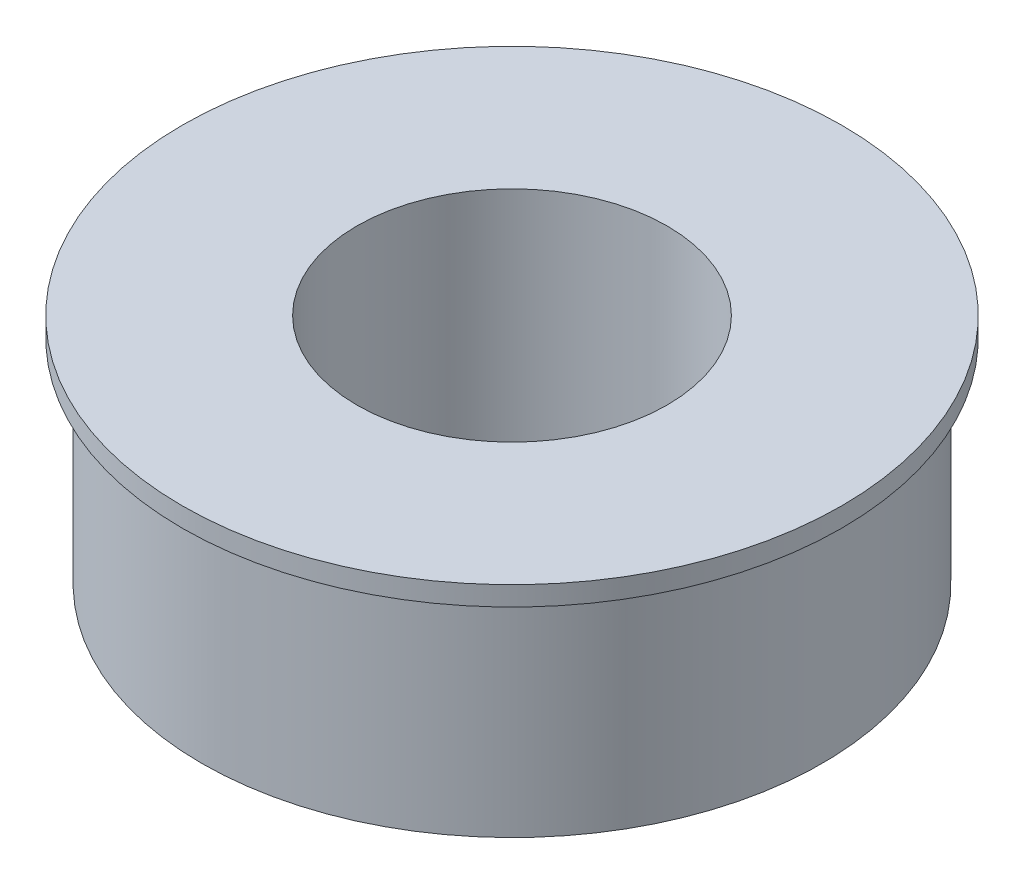
SolidWorks part; units mm, degrees
ref_plane "Front Plane" through (0, 0, 0) normal (0, 0, 1) x (1, 0, 0)
ref_plane "Top Plane" through (0, 0, 0) normal (0, 1, 0) x (1, 0, 0)
ref_plane "Right Plane" through (0, 0, 0) normal (1, 0, 0) x (0, 0, -1)
sketch "Sketch1" plane through (0, 0, 0) normal (0, 1, 0) x (1, 0, 0)
  circle A0 centre (0, 0) radius 12.7
  circle A1 centre (0, 0) radius 25.4
  dimension "D1" = 25.4
  dimension "D2" = 50.8
extrude "Boss-Extrude1" add sketch "Sketch1" along normal blind 17.4625
sketch "Sketch2" plane through (0, 17.4625, 0) normal (0, 1, 0) x (1, 0, 0)
  circle A0 centre (0, 0) radius 26.9875
  circle A1 centre (0, 0) radius 12.7
  dimension "D1" = 53.975
  dimension "D2" = 25.4
extrude "Boss-Extrude2" add sketch "Sketch2" along normal blind 1.5875
